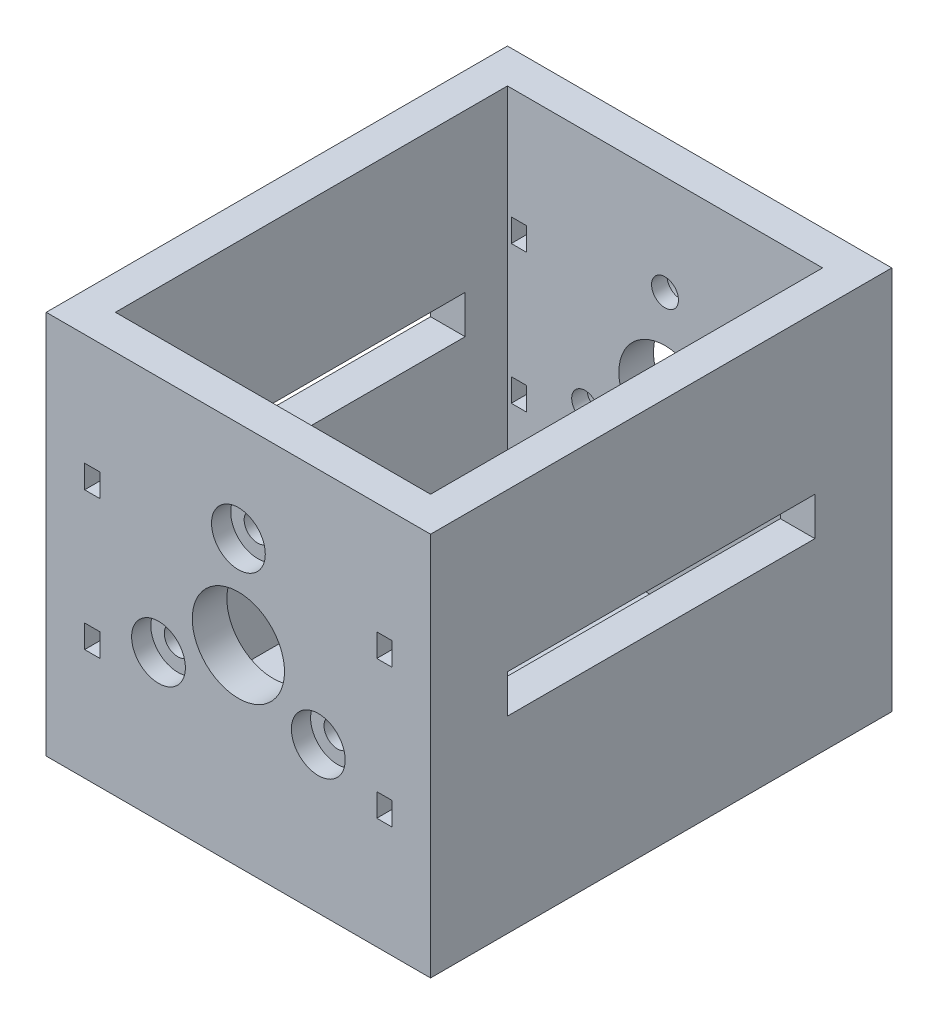
SolidWorks part; units mm, degrees
ref_plane "Front Plane" through (0, 0, 0) normal (0, 0, 1) x (1, 0, 0)
ref_plane "Top Plane" through (0, 0, 0) normal (0, 1, 0) x (1, 0, 0)
ref_plane "Right Plane" through (0, 0, 0) normal (1, 0, 0) x (0, 0, -1)
sketch "Sketch1" plane through (0, 0, 0) normal (0, 0, 1) x (1, 0, 0)
  line L1 (25, -25) -> (-25, -25)
  line L2 (25, -25) -> (25, 25)
  line L3 (25, 25) -> (-25, 25)
  line L4 (-25, -25) -> (-25, 25)
  line L5 (25, -25) -> (-25, 25) construction
  line L6 (25, 25) -> (-25, -25) construction
  point P0 (0, 0)
  dimension "D1" = 50
  dimension "D2" = 50
extrude "Boss-Extrude1" add sketch "Sketch1" along normal mid plane 60
ref_plane "Plane1" through (0, 0, 30) normal (0, 0, 1) x (1, 0, 0)
sketch "Sketch3" plane through (0, 0, 30) normal (0, 0, 1) x (1, 0, 0)
  circle A0 centre (0, 0) radius 6
  dimension "D1" = 12
extrude "Cut-Extrude1" cut sketch "Sketch3" against normal blind 70
sketch "Sketch4" plane through (0, 0, 30) normal (0, 0, 1) x (1, 0, 0)
  line L0 (-23.4706, 0) -> (22.7036, 0) construction
  line L1 (0, 23.8924) -> (0, -23.1254) construction
  line L3 (12, -0.5) -> (17, -0.5)
  line L4 (12, -0.5) -> (12, 0.5)
  line L5 (12, 0.5) -> (17, 0.5)
  line L6 (17, -0.5) -> (17, 0.5)
  line L7 (12, -0.5) -> (17, 0.5) construction
  line L8 (12, 0.5) -> (17, -0.5) construction
  point P5 (14.5, 0)
  dimension "D1" = 5
  dimension "D2" = 1
  dimension "D3" = 12
extrude "Cut-Extrude2" [suppressed] cut sketch "Sketch4" against normal blind 70
pattern_circular "CirPattern1" [suppressed] count 4 over 360
ref_plane "Plane2" through (0, 25, 0) normal (0, 1, 0) x (1, 0, 0)
sketch "Sketch5" plane through (0, 25, 0) normal (0, 1, 0) x (1, 0, 0)
  line L1 (20.5, -25.5) -> (-20.5, -25.5)
  line L2 (20.5, -25.5) -> (20.5, 25.5)
  line L3 (20.5, 25.5) -> (-20.5, 25.5)
  line L4 (-20.5, -25.5) -> (-20.5, 25.5)
  line L5 (20.5, -25.5) -> (-20.5, 25.5) construction
  line L6 (20.5, 25.5) -> (-20.5, -25.5) construction
  point P0 (0, 0)
  dimension "D1" = 41
  dimension "D2" = 51
extrude "Cut-Extrude3" cut sketch "Sketch5" against normal blind 48
sketch "Sketch6" plane through (0, 0, 30) normal (0, 0, 1) x (1, 0, 0)
  line L0 (0, 21.2323) -> (0, -19.4194) construction
  line L1 (-20.012, 0) -> (20.9882, 0) construction
  circle A0 centre (10, 0) radius 1.75
  dimension "D1" = 3.5
  dimension "D2" = 10
extrude "Cut-Extrude4" [suppressed] cut sketch "Sketch6" against normal blind 70
pattern_circular "CirPattern2" [suppressed] count 4 over 360
sketch "Sketch7" plane through (0, 0, 30) normal (0, 0, 1) x (1, 0, 0)
  line L0 (0, 18.3037) -> (0, -15.3054) construction
  line L1 (-19.4542, 0) -> (23.0801, 0) construction
  circle A0 centre (0, 12) radius 1.75
  dimension "D1" = 3.5
  dimension "D2" = 12
extrude "Cut-Extrude5" cut sketch "Sketch7" against normal blind 60
pattern_circular "CirPattern3" count 3 over 360 about axis through (0, 0, 0) along (0, 0, 1) of "Cut-Extrude5"
sketch "Sketch8" plane through (0, 0, 30) normal (0, 0, 1) x (1, 0, 0)
  line L1 (18, 10.5) -> (20, 10.5)
  line L2 (18, 10.5) -> (18, 7.5)
  line L3 (18, 7.5) -> (20, 7.5)
  line L4 (20, 10.5) -> (20, 7.5)
  line L5 (18, 10.5) -> (20, 7.5) construction
  line L6 (18, 7.5) -> (20, 10.5) construction
  point P0 (19, 9)
  dimension "D1" = 3
  dimension "D2" = 2
  dimension "D3" = 19
  dimension "D4" = 7.5
extrude "Cut-Extrude6" cut sketch "Sketch8" against normal blind 60
mirror "Mirror1" about plane through (0, 0, 0) normal (0, 1, 0) of "Cut-Extrude6" second plane through (0, 0, 0) second plane normal (1, 0, 0)
ref_plane "Plane3" through (25, 0, 0) normal (1, 0, 0) x (0, 0, -1)
sketch "Sketch9" plane through (25, 0, 0) normal (1, 0, 0) x (0, 0, -1)
  line L0 (0, 0) -> (0, 4) construction
  line L10 (20, 4.5) -> (-20, 4.5)
  line L11 (20, 4.5) -> (20, -0.5)
  line L12 (20, -0.5) -> (-20, -0.5)
  line L13 (-20, 4.5) -> (-20, -0.5)
  line L14 (20, 4.5) -> (-20, -0.5) construction
  line L15 (20, -0.5) -> (-20, 4.5) construction
  point P2 (0, 2)
  dimension "D1" = 40
  dimension "D2" = 5
  dimension "D3" = 2
extrude "Cut-Extrude7" cut sketch "Sketch9" against normal blind 60
ref_plane "Plane4" through (0, 0, 30) normal (0, 0, 1) x (1, 0, 0)
sketch "Sketch10" plane through (0, 0, 30) normal (0, 0, 1) x (1, 0, 0)
  circle A0 centre (0, 12) radius 3.5
  dimension "D1" = 7
extrude "Cut-Extrude8" cut sketch "Sketch10" against normal blind 2.5
pattern_circular "CirPattern4" count 3 over 360 about axis through (0, 0, 0) along (0, 0, 1) of "Cut-Extrude8"
mirror "Mirror2" about plane through (0, 0, 0) normal (0, 0, 1) of "CirPattern4", "Cut-Extrude8"
